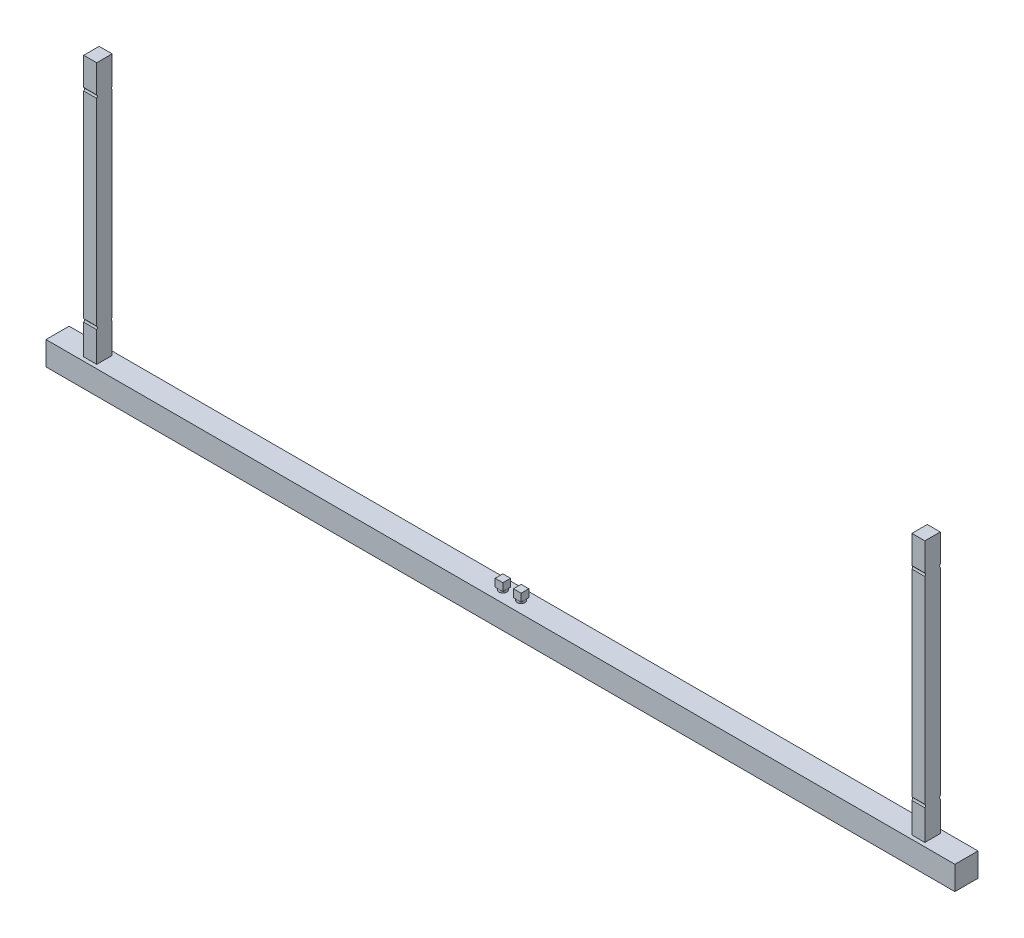
SolidWorks part; units mm, degrees
material "1.0143 (S275J0)"
ref_plane "Plano frontal" through (0, 0, 0) normal (0, 0, 1) x (1, 0, 0)
ref_plane "Plano superior" through (0, 0, 0) normal (0, 1, 0) x (1, 0, 0)
ref_plane "Plano direito" through (0, 0, 0) normal (1, 0, 0) x (0, 0, -1)
sketch "Esboço1" plane through (0, 0, 0) normal (0, 0, 1) x (1, 0, 0)
  line L0 (0, 0) -> (5900, 0)
  line L1 (0, 0) -> (0, 154)
  line L2 (0, 154) -> (5900, 154)
  line L3 (5900, 154) -> (5900, 0)
  dimension "D1" = 5900
  dimension "D2" = 154
extrude "Ressalto-extrusão1" add sketch "Esboço1" along normal blind 150
sketch "Esboço3" plane through (0, 0, 0) normal (0, 1, 0) x (1, 0, 0)
  line L0 (5680, -25) -> (5680, -125)
  line L5 (5680, -125) -> (5595.76, -125)
  line L11 (5595.76, -125) -> (5595.76, -25)
  line L16 (5595.76, -25) -> (5680, -25)
  line L17 (5900, -150) -> (5900, 0) construction
  line L18 (5900, 0) -> (0, 0) construction
  line L29 (0, -150) -> (0, 0) construction
  line L31 (220, -25) -> (304.24, -25)
  line L32 (220, -25) -> (220, -125)
  line L33 (220, -125) -> (304.24, -125)
  line L34 (304.24, -25) -> (304.24, -125)
  dimension "D1" = 100
  dimension "D2" = 100
  dimension "D3" = 220
  dimension "D4" = 84.24
  dimension "D5" = 84.24
  dimension "D6" = 25
  dimension "D7" = 25
  dimension "D8" = 220
extrude "Ressalto-extrusão2" add sketch "Esboço3" along normal blind 1849.72
sketch "Esboço4" plane through (0, 0, 0) normal (1, 0, 0) x (0, 0, -1)
  circle A0 centre (-16.4893, 1658.94) radius 12.8924
  circle A1 centre (-133.5107, 1658.94) radius 12.8924
  circle A2 centre (-16.4893, 358.9) radius 12.89
  circle A3 centre (-133.5107, 358.9) radius 12.89
  dimension "D2" = 1300.04
  dimension "D3" = 25.78
  dimension "D1" = 190.78
extrude "Corte-extrusão2" cut sketch "Esboço4" along normal through all
sketch "Esboço5" plane through (0, 0, 0) normal (0, 1, 0) x (1, 0, 0)
  circle A0 centre (3008.9558, -75) radius 25
  circle A1 centre (2891.0442, -75) radius 25
  dimension "D1" = 50
extrude "Ressalto-extrusão3" add sketch "Esboço5" along normal blind 170
sketch "Esboço7" plane through (0, 170, 0) normal (0, 1, 0) x (1, 0, 0)
  line L12 (2984.1757, -99.9832) -> (3034.1757, -99.9832)
  line L13 (3034.1757, -99.9832) -> (3034.1757, -49.9832)
  line L14 (3034.1757, -49.9832) -> (2984.1757, -49.9832)
  line L15 (2984.1757, -49.9832) -> (2984.1757, -99.9832)
  line L17 (2915.9473, -100.2643) -> (2915.9473, -50.2643)
  line L18 (2915.9473, -50.2643) -> (2865.9473, -50.2643)
  line L19 (2865.9473, -50.2643) -> (2865.9473, -100.2643)
  line L20 (2865.9473, -100.2643) -> (2915.9473, -100.2643)
  point P4 (2921.2294, -45.1047)
  point P5 (2978.2294, -105.4606)
  dimension "D1" = 50
  dimension "D2" = 50
extrude "Ressalto-extrusão4" add sketch "Esboço7" along normal blind 50
